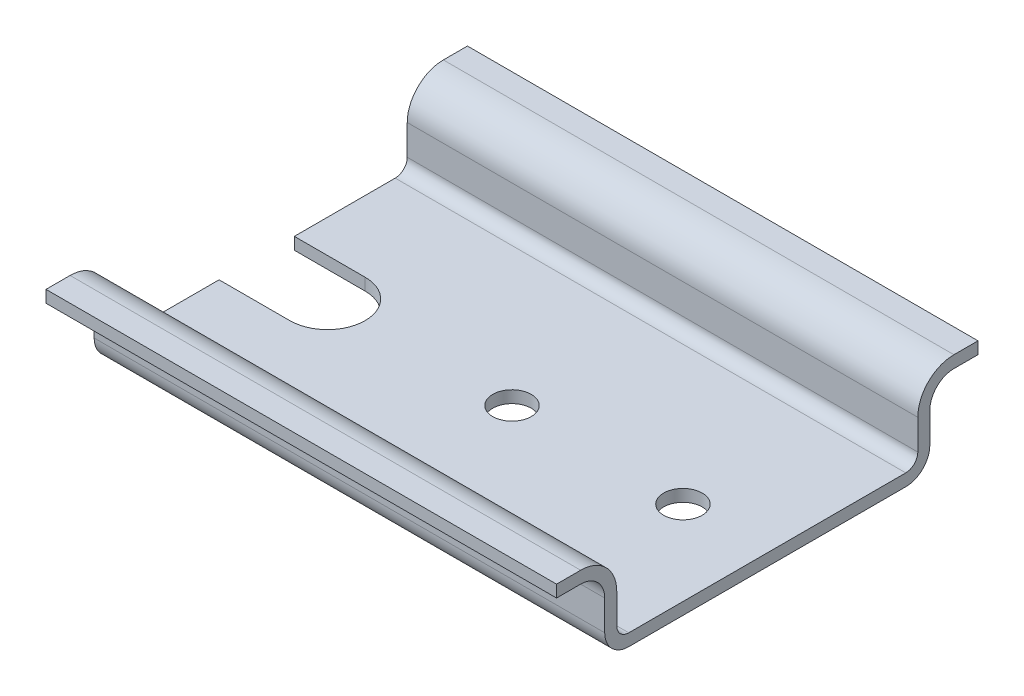
SolidWorks part; units mm, degrees
ref_plane "Front Plane" through (0, 0, 0) normal (0, 0, 1) x (1, 0, 0)
ref_plane "Top Plane" through (0, 0, 0) normal (0, 1, 0) x (1, 0, 0)
ref_plane "Right Plane" through (0, 0, 0) normal (1, 0, 0) x (0, 0, -1)
sketch "Sketch1" plane through (0, 0, 0) normal (1, 0, 0) x (0, 0, -1)
  line L0 (0, 0) -> (0, 18.2344) construction
  line L1 (0, 0) -> (26.621, 0) construction
  line L2 (-11.5, 0) -> (11.5, 0)
  line L3 (13.5, 2) -> (13.5, 4.5)
  line L4 (15.5, 6.5) -> (17.5, 6.5)
  line L5 (-13.5, 2) -> (-13.5, 4.5)
  line L6 (-15.5, 6.5) -> (-17.5, 6.5)
  arc A0 (13.5, 2) -> (11.5, 0) centre (11.5, 2) cw
  arc A1 (15.5, 6.5) -> (13.5, 4.5) centre (15.5, 4.5) ccw
  arc A2 (-13.5, 2) -> (-11.5, 0) centre (-11.5, 2) ccw
  arc A3 (-15.5, 6.5) -> (-13.5, 4.5) centre (-15.5, 4.5) cw
  point P9 (13.5, 0)
  dimension "D1" = 2
  dimension "D3" = 2
  dimension "D2" = 6.5
  dimension "D4" = 35
  dimension "D5" = 27
extrude "Extrude-Thin1" add sketch "Sketch1" along normal blind 42.4 thin thin type one direction wall 1
sketch "Sketch2" plane through (0, 0, 0) normal (0, -1, 0) x (1, 0, 0)
  line L0 (0, 6.6969) -> (0, 0) construction
  line L1 (0, 0) -> (9.9599, 0) construction
  line L2 (-5.875, 3.125) -> (5.875, 3.125)
  line L3 (-5.875, -3.125) -> (5.875, -3.125)
  arc A0 (5.875, 3.125) -> (5.875, -3.125) centre (5.875, 0) cw
  arc A1 (-5.875, 3.125) -> (-5.875, -3.125) centre (-5.875, 0) ccw
  point P6 (0, 3.125)
  point P12 (0, -3.125)
  dimension "D2" = 11.75
  dimension "D1" = 6.25
extrude "Cut-Extrude1" cut sketch "Sketch2" against normal up to next
sketch "Szkic1" plane through (0, 0, 0) normal (0, -1, 0) x (1, 0, 0)
  circle A0 centre (35.3965, 0) radius 1.6
  circle A1 centre (21.2, 0) radius 1.6
extrude "Wytnij-wyciągnięcie1" cut sketch "Szkic1" against normal through all
